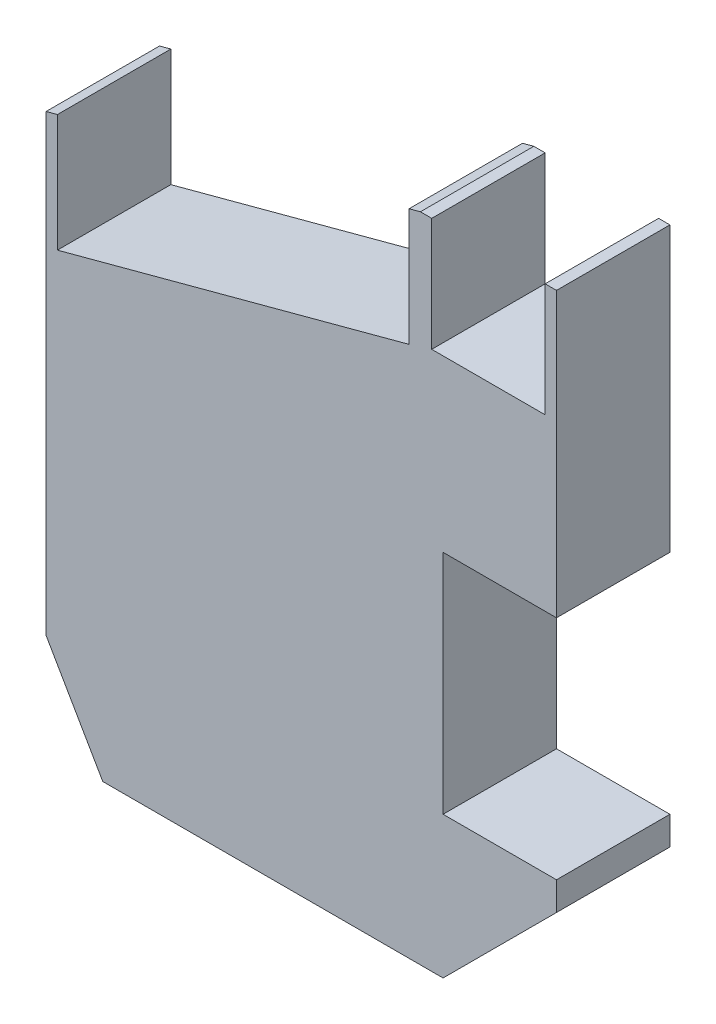
SolidWorks part; units mm, degrees
ref_plane "Front Plane" through (0, 0, 0) normal (0, 0, 1) x (1, 0, 0)
ref_plane "Top Plane" through (0, 0, 0) normal (0, 1, 0) x (1, 0, 0)
ref_plane "Right Plane" through (0, 0, 0) normal (1, 0, 0) x (0, 0, -1)
sketch "Sketch1" plane through (0, 0, 0) normal (0, 0, 1) x (1, 0, 0)
  line L0 (0, 0) -> (60, 0)
  line L1 (60, 0) -> (80, 20)
  line L2 (80, 20) -> (80, 115)
  line L3 (80, 115) -> (56, 115)
  line L4 (-10, 97.3154) -> (56, 115)
  line L5 (-10, 97.3154) -> (-10, 17.3154)
  line L6 (-10, 17.3154) -> (0, 0)
  line L7 (0, 0) -> (1.9645, -0.4911)
  dimension "D1" = 60
  dimension "D2" = 24
  dimension "D3" = 90
  dimension "D4" = 20
  dimension "D5" = 80
  dimension "D6" = 95
  dimension "D7" = 135
extrude "Boss-Extrude1" add sketch "Sketch1" along normal blind 20
sketch "Sketch2" plane through (0, 0, 20) normal (0, 0, 1) x (1, 0, 0)
  line L0 (58, 115) -> (58, 95)
  line L1 (80, 115) -> (56, 115) construction
  line L2 (58, 95) -> (78, 95)
  line L3 (78, 95) -> (78, 115)
  line L4 (-8, 97.8513) -> (-8, 77.1457)
  line L6 (-8, 77.1457) -> (54, 93.7586)
  line L7 (54, 93.7586) -> (54, 114.4641)
  line L8 (-8, 97.8513) -> (54, 114.4641)
  line L9 (-10, 97.3154) -> (-10, 17.3154) construction
  line L10 (80, 25) -> (60, 25)
  line L11 (80, 20) -> (80, 115) construction
  line L12 (60, 25) -> (60, 65)
  line L13 (60, 65) -> (80, 65)
  line L14 (80, 65) -> (80, 25)
  point P21 (0, 0)
  point P22 (0, 0)
  dimension "D1" = 2
  dimension "D2" = 2
  dimension "D3" = 20
  dimension "D4" = 20
  dimension "D5" = 2
  dimension "D6" = 2
  dimension "D7" = 5
  dimension "D8" = 40
  dimension "D9" = 20
extrude "Cut-Extrude1" cut sketch "Sketch2" against normal blind 20 and the other way through all
